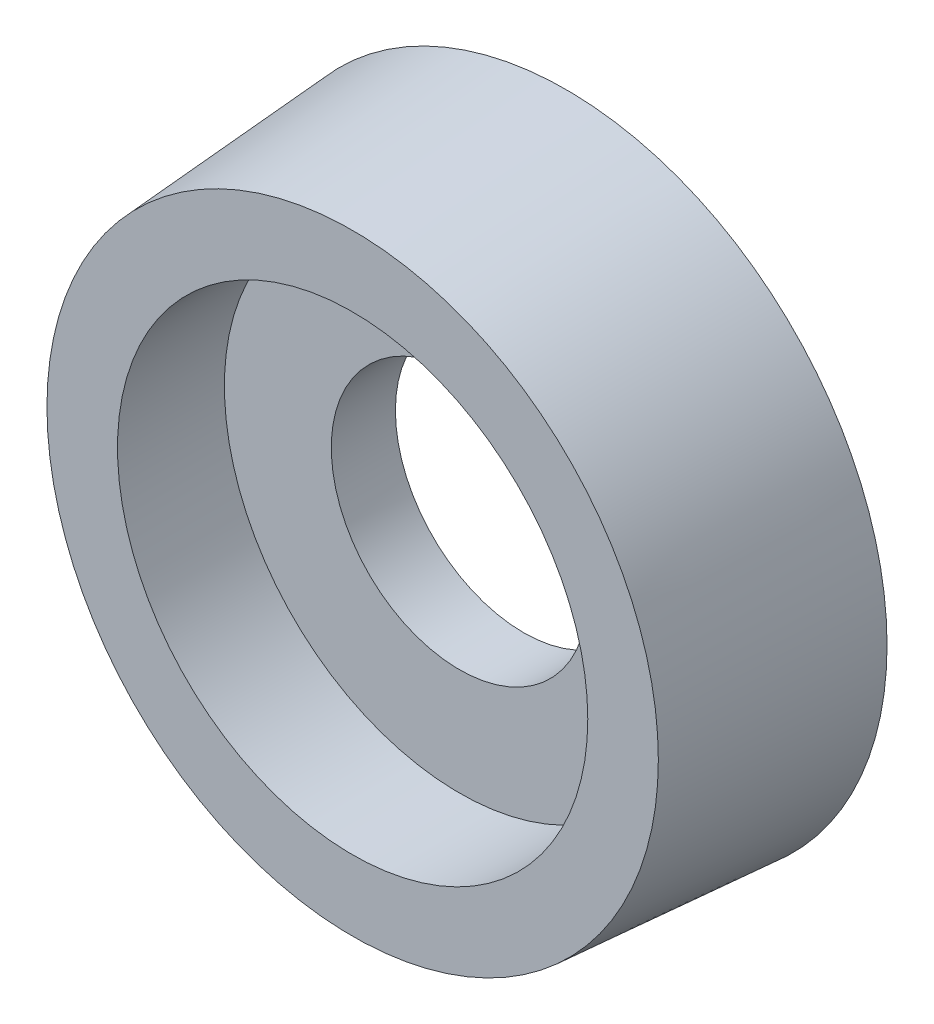
SolidWorks part; units mm, degrees
ref_plane "Спереди" through (0, 0, 0) normal (0, 0, 1) x (1, 0, 0)
ref_plane "Сверху" through (0, 0, 0) normal (0, 1, 0) x (1, 0, 0)
ref_plane "Справа" through (0, 0, 0) normal (1, 0, 0) x (0, 0, -1)
sketch "Эскиз1" plane through (0, 0, 0) normal (0, 0, 1) x (1, 0, 0)
  circle A0 centre (0, 0) radius 7.5
  dimension "D1" = 15
extrude "Бобышка-Вытянуть1" add sketch "Эскиз1" along normal blind 5 draft 4 contours A0
sketch "Эскиз3" plane through (0, 0, 0) normal (0, 0, -1) x (-1, 0, 0)
  circle A0 centre (0, 0) radius 5
  dimension "D1" = 10
extrude "Вырез-Вытянуть1" cut sketch "Эскиз3" against normal blind 1
sketch "Эскиз4" plane through (0, 0, 5) normal (0, 0, 1) x (1, 0, 0)
  circle A0 centre (0, 0) radius 5.5
  dimension "D1" = 11
extrude "Вырез-Вытянуть2" cut sketch "Эскиз4" against normal blind 2.5
sketch "Эскиз5" plane through (0, 0, 2.5) normal (0, 0, 1) x (1, 0, 0)
  circle A0 centre (0, 0) radius 3
  dimension "D1" = 6
extrude "Вырез-Вытянуть3" cut sketch "Эскиз5" against normal through all both and the other way through all
